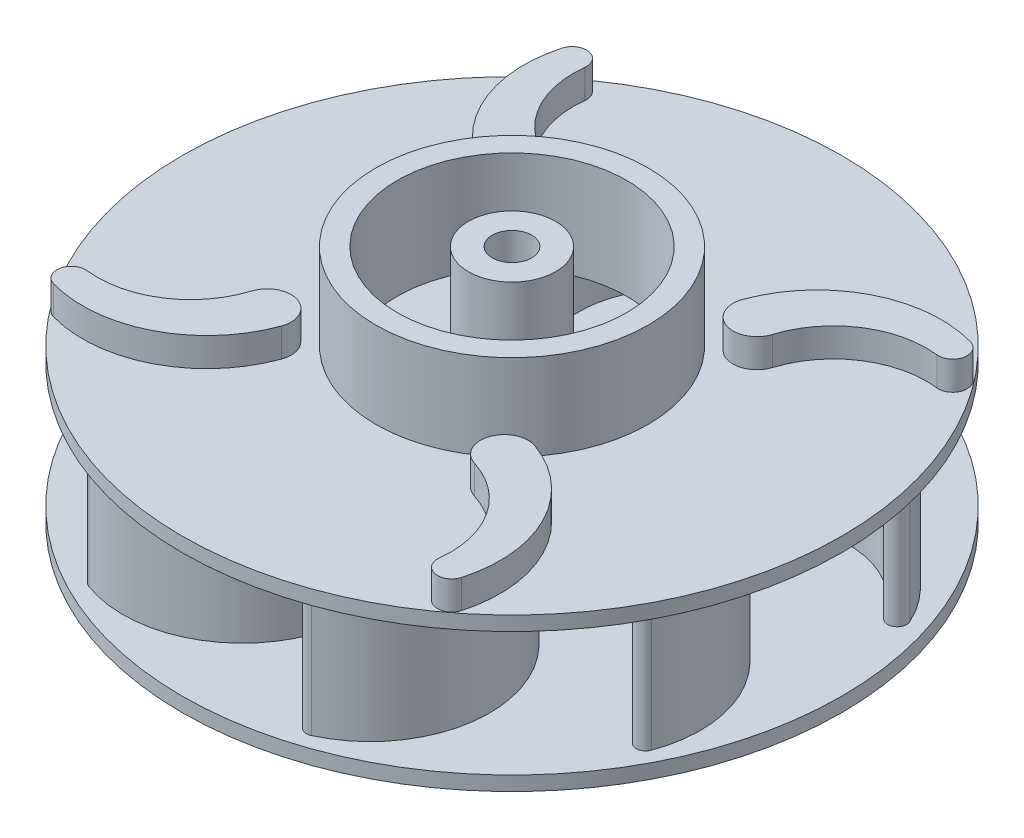
SolidWorks part; units mm, degrees
ref_plane "Front Plane" through (0, 0, 0) normal (0, 0, 1) x (1, 0, 0)
ref_plane "Top Plane" through (0, 0, 0) normal (0, 1, 0) x (1, 0, 0)
ref_plane "Right Plane" through (0, 0, 0) normal (1, 0, 0) x (0, 0, -1)
sketch "Sketch1" plane through (0, 0, 0) normal (0, 1, 0) x (1, 0, 0)
  circle A0 centre (0, 0) radius 16.5
  circle A1 centre (0, 0) radius 276
  dimension "D1" = 552
  dimension "D2" = 33
extrude "Boss-Extrude1" add sketch "Sketch1" along normal blind 12
sketch "Sketch2" plane through (0, 12, 0) normal (0, 1, 0) x (1, 0, 0)
  circle A0 centre (0, 0) radius 16.5
  circle A1 centre (0, 0) radius 36.5
  arc A2 (15.9943, -144.4275) -> (-15.9975, -143.7177) centre (0, -144) ccw
  arc A3 (-118.7852, -235.4995) -> (15.9943, -144.4275) centre (-83.97, -141.7557) ccw
  arc A4 (-114.1805, -220.2097) -> (-118.7852, -235.4995) centre (-116, -228) ccw
  arc A5 (-114.1805, -220.2097) -> (-15.9975, -143.7177) centre (-95.9851, -142.3063) ccw
  circle A6 centre (0, 0) radius 144 construction
  arc A7 (-90.816, -113.4353) -> (-112.9357, -90.3118) centre (-101.8234, -101.8234) ccw
  arc A8 (-250.5171, -82.5295) -> (-90.816, -113.4353) centre (-159.6122, -40.8606) ccw
  arc A9 (-236.4495, -74.974) -> (-250.5171, -82.5295) centre (-243.2447, -79.196) ccw
  arc A10 (-236.4495, -74.974) -> (-112.9357, -90.3118) centre (-168.4975, -32.7541) ccw
  circle A11 centre (0, 0) radius 144 construction
  arc A12 (-144.4275, -15.9943) -> (-143.7177, 15.9975) centre (-144, 0) ccw
  arc A13 (-235.4995, 118.7852) -> (-144.4275, -15.9943) centre (-141.7557, 83.97) ccw
  arc A14 (-220.2097, 114.1805) -> (-235.4995, 118.7852) centre (-228, 116) ccw
  arc A15 (-220.2097, 114.1805) -> (-143.7177, 15.9975) centre (-142.3063, 95.9851) ccw
  circle A16 centre (0, 0) radius 144 construction
  arc A17 (-113.4353, 90.816) -> (-90.3118, 112.9357) centre (-101.8234, 101.8234) ccw
  arc A18 (-82.5295, 250.5171) -> (-113.4353, 90.816) centre (-40.8606, 159.6122) ccw
  arc A19 (-74.974, 236.4495) -> (-82.5295, 250.5171) centre (-79.196, 243.2447) ccw
  arc A20 (-74.974, 236.4495) -> (-90.3118, 112.9357) centre (-32.7541, 168.4975) ccw
  circle A21 centre (0, 0) radius 144 construction
  arc A22 (-15.9943, 144.4275) -> (15.9975, 143.7177) centre (0, 144) ccw
  arc A23 (118.7852, 235.4995) -> (-15.9943, 144.4275) centre (83.97, 141.7557) ccw
  arc A24 (114.1805, 220.2097) -> (118.7852, 235.4995) centre (116, 228) ccw
  arc A25 (114.1805, 220.2097) -> (15.9975, 143.7177) centre (95.9851, 142.3063) ccw
  circle A26 centre (0, 0) radius 144 construction
  arc A27 (90.816, 113.4353) -> (112.9357, 90.3118) centre (101.8234, 101.8234) ccw
  arc A28 (250.5171, 82.5295) -> (90.816, 113.4353) centre (159.6122, 40.8606) ccw
  arc A29 (236.4495, 74.974) -> (250.5171, 82.5295) centre (243.2447, 79.196) ccw
  arc A30 (236.4495, 74.974) -> (112.9357, 90.3118) centre (168.4975, 32.7541) ccw
  circle A31 centre (0, 0) radius 144 construction
  arc A32 (144.4275, 15.9943) -> (143.7177, -15.9975) centre (144, 0) ccw
  arc A33 (235.4995, -118.7852) -> (144.4275, 15.9943) centre (141.7557, -83.97) ccw
  arc A34 (220.2097, -114.1805) -> (235.4995, -118.7852) centre (228, -116) ccw
  arc A35 (220.2097, -114.1805) -> (143.7177, -15.9975) centre (142.3063, -95.9851) ccw
  circle A36 centre (0, 0) radius 144 construction
  arc A37 (113.4353, -90.816) -> (90.3118, -112.9357) centre (101.8234, -101.8234) ccw
  arc A38 (82.5295, -250.5171) -> (113.4353, -90.816) centre (40.8606, -159.6122) ccw
  arc A39 (74.974, -236.4495) -> (82.5295, -250.5171) centre (79.196, -243.2447) ccw
  arc A40 (74.974, -236.4495) -> (90.3118, -112.9357) centre (32.7541, -168.4975) ccw
  circle A41 centre (0, 0) radius 144 construction
  point P79 (0, 0)
  dimension "D1" = 20
  dimension "D2" = 33
  dimension "D3" = 16
  dimension "D4" = 8
  dimension "D5" = 116
  dimension "D7" = 80
  dimension "D8" = 100
  dimension "D9" = 288
  dimension "D6" = 84
  dimension "D10" = 8
extrude "Boss-Extrude2" add sketch "Sketch2" along normal blind 104
sketch "Sketch4" plane through (0, 116, 0) normal (0, 1, 0) x (1, 0, 0)
  circle A0 centre (0, 0) radius 276
  circle A1 centre (0, 0) radius 96
  dimension "D1" = 192
  dimension "D2" = 552
extrude "Boss-Extrude6" add sketch "Sketch4" along normal blind 12
sketch "Sketch5" plane through (0, 128, 0) normal (0, 1, 0) x (1, 0, 0)
  arc A0 (170.8305, -212.9397) -> (106.0769, -86.8689) centre (70.7429, -184.6825) ccw
  arc A1 (106.0769, -86.8689) -> (93.2851, -124.759) centre (99.2819, -105.6792) ccw
  arc A2 (147.364, -208.278) -> (170.8305, -212.9397) centre (159.2819, -209.6792) ccw
  arc A3 (147.364, -208.278) -> (93.2851, -124.759) centre (69.8976, -199.1702) ccw
  circle A4 centre (0, 0) radius 145 construction
  arc A5 (-212.9397, -170.8305) -> (-86.8689, -106.0769) centre (-184.6825, -70.7429) ccw
  arc A6 (-86.8689, -106.0769) -> (-124.759, -93.2851) centre (-105.6792, -99.2819) ccw
  arc A7 (-208.278, -147.364) -> (-212.9397, -170.8305) centre (-209.6792, -159.2819) ccw
  arc A8 (-208.278, -147.364) -> (-124.759, -93.2851) centre (-199.1702, -69.8976) ccw
  circle A9 centre (0, 0) radius 145 construction
  arc A10 (-170.8305, 212.9397) -> (-106.0769, 86.8689) centre (-70.7429, 184.6825) ccw
  arc A11 (-106.0769, 86.8689) -> (-93.2851, 124.759) centre (-99.2819, 105.6792) ccw
  arc A12 (-147.364, 208.278) -> (-170.8305, 212.9397) centre (-159.2819, 209.6792) ccw
  arc A13 (-147.364, 208.278) -> (-93.2851, 124.759) centre (-69.8976, 199.1702) ccw
  circle A14 centre (0, 0) radius 145 construction
  arc A15 (212.9397, 170.8305) -> (86.8689, 106.0769) centre (184.6825, 70.7429) ccw
  arc A16 (86.8689, 106.0769) -> (124.759, 93.2851) centre (105.6792, 99.2819) ccw
  arc A17 (208.278, 147.364) -> (212.9397, 170.8305) centre (209.6792, 159.2819) ccw
  arc A18 (208.278, 147.364) -> (124.759, 93.2851) centre (199.1702, 69.8976) ccw
  circle A19 centre (0, 0) radius 145 construction
  point P8 (99.2819, 80.3327)
  point P42 (0, 0)
  dimension "D2" = 60
  dimension "D3" = 104
  dimension "D1" = 104
  dimension "D4" = 78
  dimension "D5" = 20
  dimension "D6" = 12
  dimension "D7" = 290
  dimension "D8" = 4
extrude "Boss-Extrude7" add sketch "Sketch5" along normal blind 24
sketch "Sketch6" plane through (0, 128, 0) normal (0, 1, 0) x (1, 0, 0)
  circle A0 centre (0, 0) radius 96
  circle A1 centre (0, 0) radius 114
  dimension "D1" = 18
  dimension "D2" = 192
extrude "Boss-Extrude8" add sketch "Sketch6" along normal blind 72
fillet "Fillet1" radius 14 1 edges at (0, 12, 36.5)
sketch "Sketch7" plane through (0, 116, 0) normal (0, 1, 0) x (1, 0, 0)
  circle A0 centre (0, 0) radius 16.5
  circle A1 centre (0, 0) radius 36.5
  dimension "D1" = 20
  dimension "D2" = 33
extrude "Boss-Extrude9" add sketch "Sketch7" along normal blind 84
